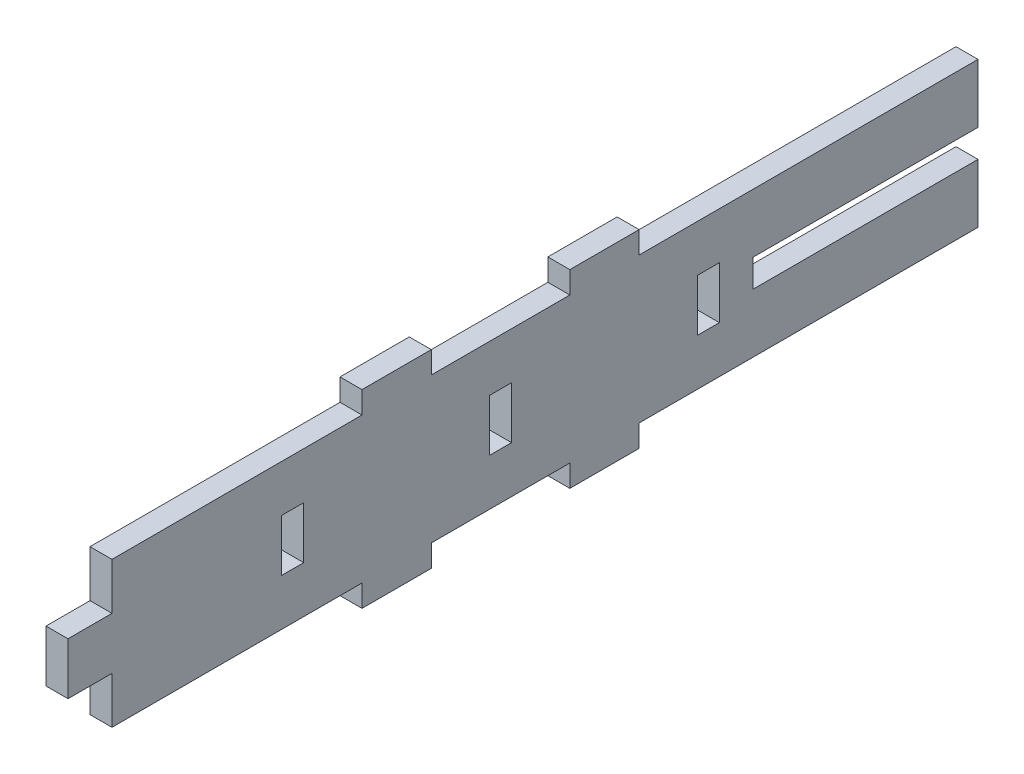
SolidWorks part; units mm, degrees
ref_plane "Front Plane" through (0, 0, 0) normal (0, 0, 1) x (1, 0, 0)
ref_plane "Top Plane" through (0, 0, 0) normal (0, 1, 0) x (1, 0, 0)
ref_plane "Right Plane" through (0, 0, 0) normal (1, 0, 0) x (0, 0, -1)
sketch "Sketch1" plane through (0, 0, 0) normal (1, 0, 0) x (0, 0, -1)
  line L1 (125, -21) -> (-125, -21)
  line L2 (125, -21) -> (125, 21)
  line L3 (125, 21) -> (-125, 21)
  line L4 (-125, -21) -> (-125, 21)
  line L5 (125, -21) -> (-125, 21) construction
  line L6 (125, 21) -> (-125, -21) construction
  line L7 (-125, -7.5) -> (-137.7, -7.5)
  line L8 (-125, -7.5) -> (-125, 7.5)
  line L9 (-125, 7.5) -> (-137.7, 7.5)
  line L10 (-137.7, -7.5) -> (-137.7, 7.5)
  line L11 (-125, -7.5) -> (-137.7, 7.5) construction
  line L12 (-125, 7.5) -> (-137.7, -7.5) construction
  point P0 (0, 0)
  point P6 (-131.35, 0)
  point P16 (0, 0)
  point P17 (0, 0)
  dimension "D1" = 12.7
  dimension "D2" = 15
  dimension "D3" = 250
  dimension "D4" = 42
extrude "Boss-Extrude1" add sketch "Sketch1" along normal blind 6.35
sketch "Sketch2" plane through (6.35, 0, 0) normal (1, 0, 0) x (0, 0, -1)
  line L0 (-125, 7.5) -> (-125, 21) construction
  line L1 (-69.65, -7.5) -> (-76, -7.5)
  line L2 (-69.65, -7.5) -> (-69.65, 7.5)
  line L3 (-69.65, 7.5) -> (-76, 7.5)
  line L4 (-76, -7.5) -> (-76, 7.5)
  line L5 (-69.65, -7.5) -> (-76, 7.5) construction
  line L6 (-69.65, 7.5) -> (-76, -7.5) construction
  point P0 (-72.825, 0)
  point P7 (-125, 14.25)
  point P8 (0, 0)
  dimension "D1" = 49
  dimension "D2" = 6.35
  dimension "D3" = 15
extrude "Cut-Extrude1" cut sketch "Sketch2" against normal through all
pattern_linear "LPattern1" count 3 spacing 60 along (0, 0, -1) of "Cut-Extrude1"
sketch "Sketch3" plane through (6.35, 0, 0) normal (1, 0, 0) x (0, 0, -1)
  line L0 (125, -21) -> (125, 21) construction
  line L1 (125, -4) -> (60, -4)
  line L2 (125, -4) -> (125, 4)
  line L3 (125, 4) -> (60, 4)
  line L4 (60, -4) -> (60, 4)
  line L5 (125, -4) -> (60, 4) construction
  line L6 (125, 4) -> (60, -4) construction
  point P0 (92.5, 0)
  point P7 (0, 0)
  dimension "D1" = 65
  dimension "D2" = 8
extrude "Cut-Extrude2" cut sketch "Sketch3" against normal through all
sketch "Sketch4" plane through (6.35, 0, 0) normal (1, 0, 0) x (0, 0, -1)
  line L0 (125, 21) -> (-125, 21) construction
  line L18 (-69.65, -7.5) -> (-16, -7.5) construction
  line L23 (-32.825, 21) -> (-52.825, 21)
  line L24 (-32.825, 21) -> (-32.825, 27.35)
  line L25 (-32.825, 27.35) -> (-52.825, 27.35)
  line L26 (-52.825, 21) -> (-52.825, 27.35)
  line L27 (-32.825, 21) -> (-52.825, 27.35) construction
  line L28 (-32.825, 27.35) -> (-52.825, 21) construction
  line L29 (27.175, 21) -> (7.175, 21)
  line L30 (27.175, 21) -> (27.175, 27.35)
  line L31 (27.175, 27.35) -> (7.175, 27.35)
  line L32 (7.175, 21) -> (7.175, 27.35)
  line L33 (27.175, 21) -> (7.175, 27.35) construction
  line L34 (27.175, 27.35) -> (7.175, 21) construction
  line L35 (-9.65, -7.5) -> (44, -7.5) construction
  point P0 (-42.825, 24.175)
  point P5 (17.175, 24.175)
  point P14 (0, 0)
  point P19 (-42.825, -7.5)
  point P20 (17.175, -7.5)
  dimension "D1" = 20
  dimension "D2" = 6.35
extrude "Boss-Extrude2" add sketch "Sketch4" against normal up to surface (6.35 mm away) up to face at (0, 0, 12.825)
mirror "Mirror1" about plane through (0, 0, 0) normal (0, 1, 0) of "Boss-Extrude2"
